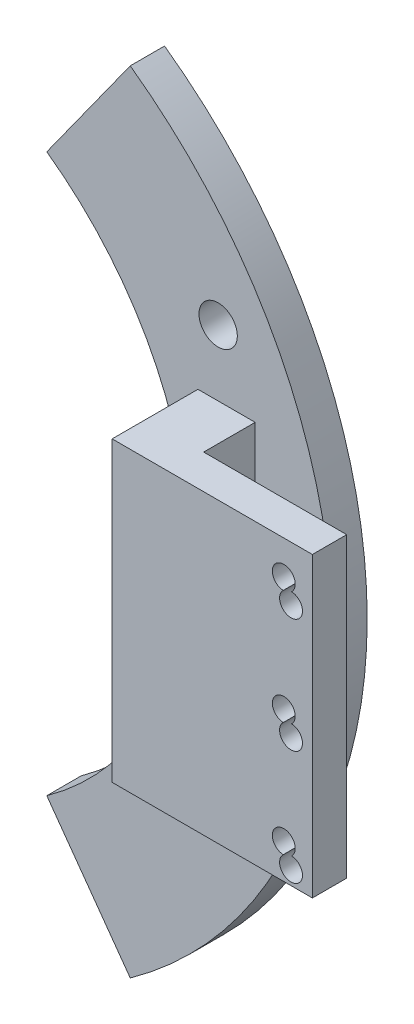
SolidWorks part; units mm, degrees
material "PEI"
ref_plane "前视基准面" through (0, 0, 0) normal (0, 0, 1) x (1, 0, 0)
ref_plane "上视基准面" through (0, 0, 0) normal (0, 1, 0) x (1, 0, 0)
ref_plane "右视基准面" through (0, 0, 0) normal (1, 0, 0) x (0, 0, -1)
other "Configuration Table"
sketch "草图1" plane through (0, 0, 0) normal (0, 0, 1) x (1, 0, 0)
  circle A0 centre (0, 0) radius 85
  circle A1 centre (0, 0) radius 60
  dimension "D1" = 170
  dimension "D2" = 120
extrude "凸台-拉伸1" add sketch "草图1" along normal blind 6
sketch "草图2" plane through (0, 0, 6) normal (0, 0, 1) x (1, 0, 0)
  line L0 (0, 0) -> (0, 90.5173) construction
  line L1 (0, 0) -> (-91.1914, 52.6494) construction
  line L2 (0, 0) -> (-88.371, -51.021) construction
  line L3 (0, 0) -> (0, -97.4369) construction
  line L4 (0, 0) -> (91.1914, 52.6494) construction
  line L5 (0, 0) -> (88.371, -51.021) construction
  circle A0 centre (0, 75) radius 3.35
  circle A1 centre (64.9519, 37.5) radius 3.35
  circle A2 centre (64.9519, -37.5) radius 3.35
  circle A3 centre (0, -75) radius 3.35
  circle A4 centre (-64.9519, -37.5) radius 3.35
  circle A5 centre (-64.9519, 37.5) radius 3.35
  dimension "D1" = 6.7
  dimension "D8" = 6.7
  dimension "D9" = 6.7
  dimension "D10" = 6.7
  dimension "D2" = 75
  dimension "D3" = 60
  dimension "D4" = 60
  dimension "D5" = 75
  dimension "D6" = 75
  dimension "D7" = 75
extrude "切除-拉伸1" cut sketch "草图2" against normal blind 10
sketch "草图3" plane through (0, 0, 6) normal (0, 0, 1) x (1, 0, 0)
  line L0 (0, 0) -> (-135.1725, 0) construction
  line L5 (0, 0) -> (0, 80.8621) construction
  line L11 (71.4195, -26.0097) -> (61.4195, -26.0097)
  line L12 (-71.4195, 25.9903) -> (-61.4195, 25.9903)
  line L16 (-71.4195, 25.9903) -> (-71.4195, -26.0097)
  line L17 (-71.4195, -26.0097) -> (-61.4195, -26.0097)
  line L18 (-61.4195, 25.9903) -> (-61.4195, -26.0097)
  line L19 (71.4195, 25.9903) -> (71.4195, -26.0097)
  line L20 (71.4195, 25.9903) -> (61.4195, 25.9903)
  line L21 (61.4195, 25.9903) -> (61.4195, -26.0097)
  point P2 (-71.4195, 0)
  dimension "D1" = 10
  dimension "D2" = 52
extrude "凸台-拉伸2" add sketch "草图3" along normal blind 15
sketch "草图8" plane through (-71.4195, 0, 0) normal (-1, 0, 0) x (0, 0, 1)
  line L0 (21, -26.0097) -> (6, -26.0097) construction
  line L1 (21, 25.9903) -> (13, 25.9903)
  line L2 (21, 25.9903) -> (21, -26.0097)
  line L3 (21, -26.0097) -> (13, -26.0097)
  line L4 (13, 25.9903) -> (13, -26.0097)
  dimension "D1" = 8
extrude "凸台-拉伸3" add sketch "草图8" along normal blind 25
sketch "草图10" plane through (71.4195, 0, 0) normal (1, 0, 0) x (0, 0, -1)
  line L0 (-21, -26.0097) -> (-6, -26.0097) construction
  line L1 (-21, 25.9903) -> (-15, 25.9903)
  line L2 (-21, 25.9903) -> (-21, -26.0097)
  line L3 (-21, -26.0097) -> (-15, -26.0097)
  line L4 (-15, 25.9903) -> (-15, -26.0097)
  dimension "D1" = 6
extrude "凸台-拉伸4" add sketch "草图10" along normal blind 25
sketch "草图11" plane through (0, 0, 21) normal (0, 0, 1) x (1, 0, 0)
  line L0 (-96.4195, -26.0097) -> (-96.4195, 25.9903) construction
  line L1 (0, 0) -> (0, 29.3779) construction
  line L2 (0, 0) -> (27.769, 0) construction
  circle A0 centre (-91.4195, 0) radius 2
  circle A1 centre (-91.4195, 20) radius 2
  circle A2 centre (91.4195, 0) radius 2
  circle A3 centre (91.4195, 20) radius 2
  circle A4 centre (91.4195, -20) radius 2
  circle A5 centre (-91.4195, -20) radius 2
  dimension "D1" = 5
  dimension "D2" = 20
extrude "切除-拉伸3" cut sketch "草图11" against normal blind 25
sketch "草图12" plane through (0, 0, 6) normal (0, 0, 1) x (1, 0, 0)
  line L0 (35, 48.734) -> (49.5833, 69.0398)
  line L1 (35, -90) -> (-35, -90)
  line L2 (35, -90) -> (35, -77.4597)
  line L3 (35, 90) -> (-35, 90)
  line L5 (35, -90) -> (-35, 90) construction
  line L6 (35, 90) -> (-35, -90) construction
  line L7 (-35, 90) -> (-133.6205, 90)
  line L9 (-35, -90) -> (-133.6205, -90)
  line L10 (-133.6205, 90) -> (-133.6205, -90)
  line L11 (35, -48.734) -> (49.5833, -69.0398)
  line L12 (35, -48.734) -> (35, 48.734)
  line L13 (35, 77.4597) -> (35, 90)
  circle A0 centre (0, 0) radius 60 construction
  circle A1 centre (0, 0) radius 85 construction
  arc A2 (35, -77.4597) -> (49.5833, -69.0398) centre (0, 0) ccw
  arc A3 (49.5833, 69.0398) -> (35, 77.4597) centre (0, 0) ccw
  point P0 (0, 0)
  dimension "D1" = 70
  dimension "D2" = 180
extrude "切除-拉伸4" cut sketch "草图12" against normal mid plane 100
sketch "草图6" plane through (0, 0, 26) normal (0, 0, 1) x (1, 0, 0)
  line L0 (0, 0) -> (0, 48.6782) construction
  line L1 (92.6897, -3.4598) -> (92.6897, -43.4598) construction
  line L2 (92.6897, -3.4598) -> (92.6897, 36.5402) construction
  circle A0 centre (92.6897, -3.4598) radius 2
  circle A1 centre (92.6897, -23.4598) radius 2
  circle A2 centre (92.6897, 16.5402) radius 2
  circle A3 centre (-92.6897, -23.4598) radius 2
  circle A4 centre (-92.6897, -3.4598) radius 2
  circle A5 centre (-92.6897, 16.5402) radius 2
  dimension "D1" = 4
  dimension "D2" = 20
  dimension "D4" = 4
  dimension "D5" = 4
  dimension "D3" = 20
extrude "切除-拉伸2" cut sketch "草图6" against normal blind 20
